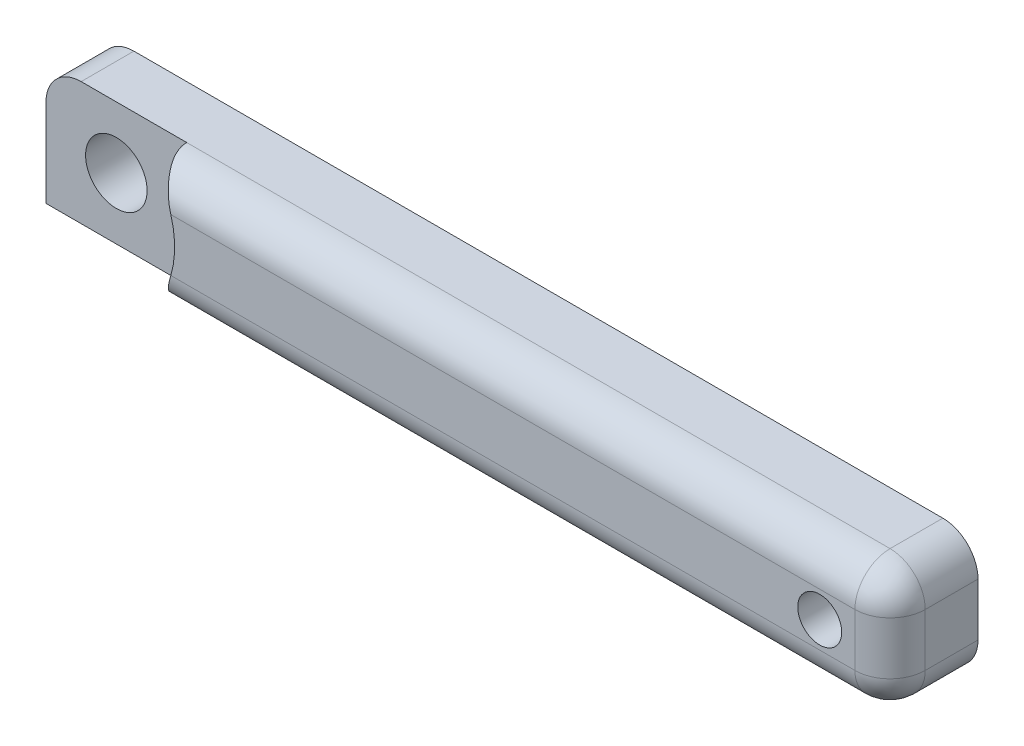
SolidWorks part; units mm, degrees
ref_plane "Front Plane" through (0, 0, 0) normal (0, 0, 1) x (1, 0, 0)
ref_plane "Top Plane" through (0, 0, 0) normal (0, 1, 0) x (1, 0, 0)
ref_plane "Right Plane" through (0, 0, 0) normal (1, 0, 0) x (0, 0, -1)
sketch "Sketch1" plane through (0, 0, 0) normal (0, 0, 1) x (1, 0, 0)
  line L0 (0, 0) -> (48, 0)
  line L1 (50, 2) -> (50, 5)
  line L2 (48, 7) -> (2, 7)
  line L3 (0, 5) -> (0, 0)
  arc A0 (2, 7) -> (0, 5) centre (2, 5) ccw
  arc A1 (48, 0) -> (50, 2) centre (48, 2) ccw
  arc A2 (50, 5) -> (48, 7) centre (48, 5) ccw
  point P7 (0, 7)
  point P10 (50, 0)
  dimension "D3" = 2
  dimension "D1" = 7
  dimension "D2" = 50
extrude "Boss-Extrude1" add sketch "Sketch1" along normal blind 5
sketch "Sketch2" plane through (0, 0, 0) normal (0, 0, -1) x (-1, 0, 0)
  line L0 (-50, 3.5) -> (-46, 3.5) construction
  line L1 (-50, 2) -> (-50, 5) construction
  circle A0 centre (-46, 3.5) radius 2.4
  point P3 (-56.2237, 3.8411)
  point P6 (-56.1237, 3.4721)
  point P7 (-56.193, 3.5)
  dimension "D1" = 4.8
  dimension "D2" = 4
extrude "Cut-Extrude1" cut sketch "Sketch2" against normal blind 3
sketch "Sketch3" plane through (0, 0, 3) normal (0, 0, -1) x (-1, 0, 0)
  circle A0 centre (-46, 3.5) radius 1.25
  dimension "D1" = 2.5
extrude "Cut-Extrude2" cut sketch "Sketch3" against normal through all
fillet "Fillet1" radius 2 7 edges at (24, 0, 5) (49.4142, 0.5858, 5) (50, 3.5, 5) (49.4142, 6.4142, 5) (25, 7, 5) (0.5858, 6.4142, 5) (0, 2.5, 5)
sketch "Sketch4" plane through (0, 0, 5) normal (0, 0, 1) x (1, 0, 0)
  line L0 (4, 7) -> (4, 0) construction
  line L1 (2, 7) -> (48, 7) construction
  line L2 (48, 0) -> (0, 0) construction
  line L3 (0, 0) -> (0, 5) construction
  circle A0 centre (4, 3.5) radius 1.75
  point P8 (4.6309, 0)
  point P9 (5.4554, 2.7475)
  dimension "D1" = 3.5
  dimension "D2" = 4
extrude "Cut-Extrude3" cut sketch "Sketch4" against normal through all
sketch "Sketch5" plane through (0, 0, 5) normal (0, 0, 1) x (1, 0, 0)
  circle A0 centre (4, 3.5) radius 5.3151
extrude "Cut-Extrude4" cut sketch "Sketch5" against normal blind 2
